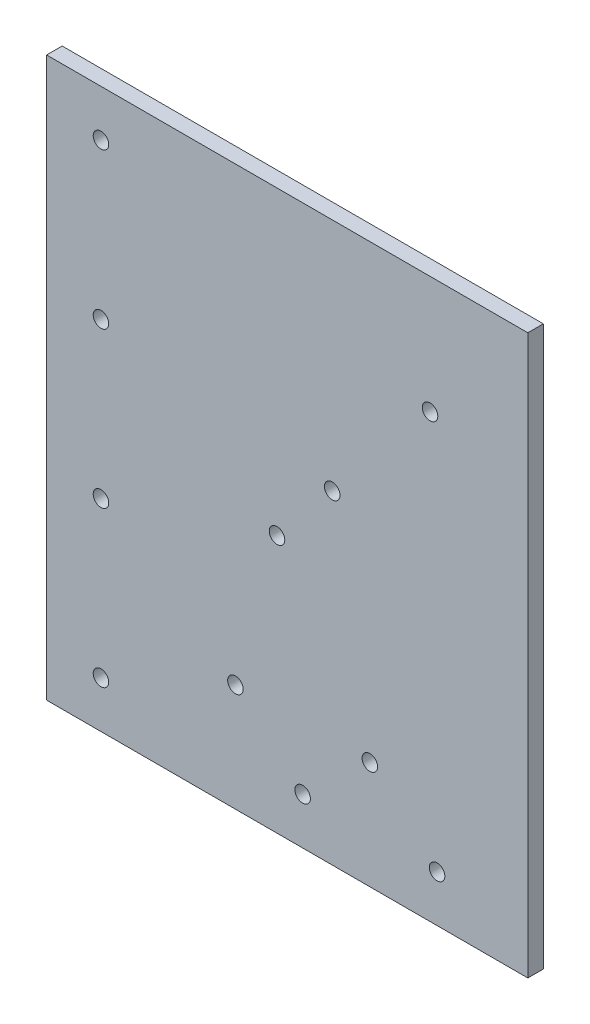
SolidWorks part; units mm, degrees
ref_plane "Front Plane" through (0, 0, 0) normal (0, 0, 1) x (1, 0, 0)
ref_plane "Top Plane" through (0, 0, 0) normal (0, 1, 0) x (1, 0, 0)
ref_plane "Right Plane" through (0, 0, 0) normal (1, 0, 0) x (0, 0, -1)
sketch "Sketch1" plane through (0, 0, 0) normal (0, 0, 1) x (1, 0, 0)
  line L1 (0, 0) -> (393.7, 0)
  line L2 (0, 0) -> (0, 457.2)
  line L3 (0, 457.2) -> (393.7, 457.2)
  line L4 (393.7, 0) -> (393.7, 457.2)
  dimension "D1" = 393.7
  dimension "D2" = 457.2
extrude "Plate" add sketch "Sketch1" along normal blind 12.7
hole_wizard "Hole" positions "Sketch4" profile "Sketch3" hole size "1/2" standard "Ansi Inch"
sketch "Sketch4" plane through (0, 0, 12.7) normal (0, 0, 1) x (1, 0, 0)
  line L0 (0, 457.2) -> (0, 0) construction
  line L1 (0, 0) -> (393.7, 0) construction
  point P0 (44.45, 38.1)
  dimension "D1" = 44.45
  dimension "D2" = 38.1
sketch "Sketch3" plane through (44.45, 38.1, 12.7) normal (1, 0, 0) x (0, -1, 0)
  line L0 (0, 0) -> (0, 29.2155)
  line L1 (0, 29.2155) -> (6.35, 25.4)
  line L2 (6.35, 25.4) -> (6.35, 0)
  line L5 (6.35, 0) -> (0, 0)
  line L10 (0, 29.2155) -> (-6.35, 25.4) construction
  line L11 (0, -6.35) -> (0, 107.95) construction
  dimension "Hole Dia." = 12.7
  dimension "Hole Depth" = 25.4
  dimension "Drill Angle" = 118
pattern_linear "標準複製排列" count 4 spacing 127 along (0, 1, 0) of "Hole"
sketch "草圖1" plane through (0, 0, 12.7) normal (0, 0, 1) x (1, 0, 0)
  line L0 (44.45, 38.1) -> (393.7, 457.2) construction
  circle A1 centre (44.45, 38.1) radius 6.35 construction
  point P2 (233.6539, 265.1447)
  point P3 (313.677, 361.1723)
  point P7 (188.4915, 210.9498)
  dimension "D1" = 225
  dimension "D2" = 125
  dimension "D3" = 125
pattern_sketch "草圖複製排列1" of "Hole" driven by "草圖1"
sketch "草圖2" plane through (0, 0, 12.7) normal (0, 0, 1) x (1, 0, 0)
  point P0 (209.45, 38.1)
  point P1 (319.45, 38.1)
  point P2 (154.45, 88.1)
  point P3 (264.45, 88.1)
  dimension "D1" = 110
  dimension "D2" = 165
  dimension "D3" = 220
  dimension "D4" = 275
  dimension "D5" = 50
pattern_sketch "草圖複製排列2" of "Hole" driven by "草圖2"
